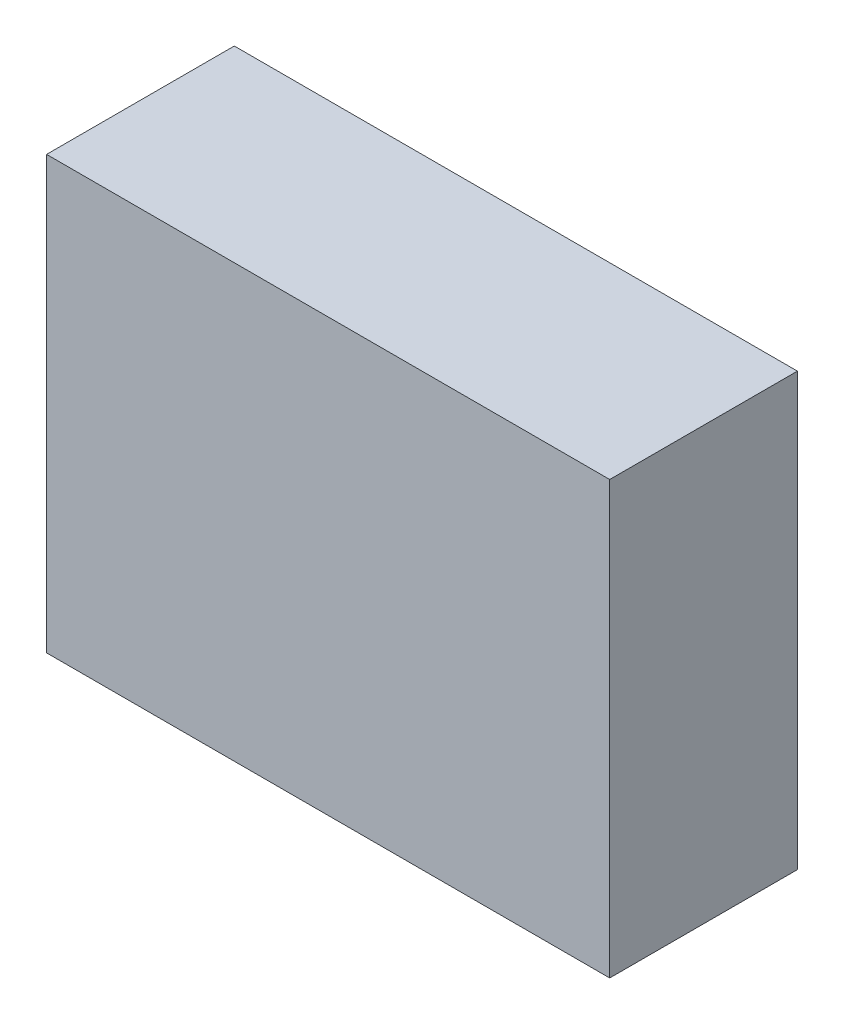
SolidWorks part; units mm, degrees
ref_plane "前视基准面" through (0, 0, 0) normal (0, 0, 1) x (1, 0, 0)
ref_plane "上视基准面" through (0, 0, 0) normal (0, 1, 0) x (1, 0, 0)
ref_plane "右视基准面" through (0, 0, 0) normal (1, 0, 0) x (0, 0, -1)
other "Configuration Table"
sketch "草图1" plane through (0, 0, 0) normal (0, 0, 1) x (1, 0, 0)
  line L1 (-25, -20) -> (35, -20)
  line L2 (-25, -20) -> (-25, 26)
  line L3 (-25, 26) -> (35, 26)
  line L4 (35, -20) -> (35, 26)
extrude "凸台-拉伸1" add sketch "草图1" along normal blind 20
